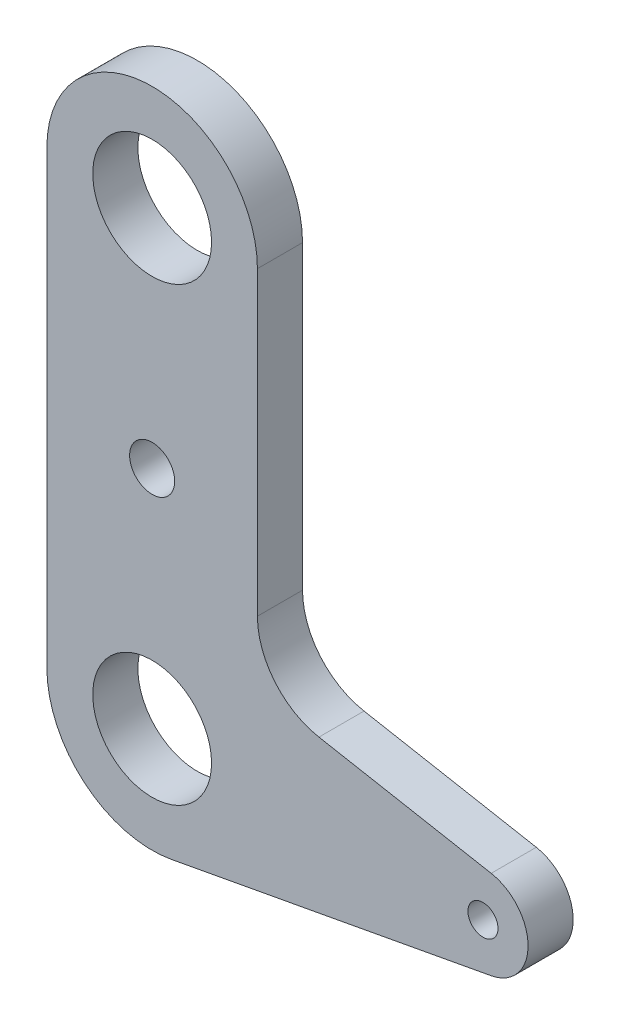
SolidWorks part; units mm, degrees
ref_plane "前视基准面" through (0, 0, 0) normal (0, 0, 1) x (1, 0, 0)
ref_plane "上视基准面" through (0, 0, 0) normal (0, 1, 0) x (1, 0, 0)
ref_plane "右视基准面" through (0, 0, 0) normal (1, 0, 0) x (0, 0, -1)
sketch "草图1" plane through (0, 0, 0) normal (0, 0, 1) x (1, 0, 0)
  line L0 (-7, 30) -> (-7, 0)
  line L1 (7, 30) -> (7, 0)
  line L2 (1.2727, 6.8833) -> (22.5455, 2.95)
  line L3 (0, 0) -> (16.3963, 0)
  line L4 (1.2727, -6.8833) -> (22.5455, -2.95)
  circle A0 centre (0, 0) radius 3.95
  circle A1 centre (0, 30) radius 3.95
  circle A3 centre (0, 30) radius 7
  circle A4 centre (0, 0) radius 7
  circle A6 centre (22, 0) radius 1
  circle A7 centre (22, 0) radius 3
  circle A8 centre (0, 15) radius 1.5
  dimension "D1" = 14
  dimension "D2" = 7.9
  dimension "D3" = 30
  dimension "D4" = 22
  dimension "D5" = 6
  dimension "D6" = 2
  dimension "D7" = 3
  dimension "D9" = 7.9
  dimension "D8" = 15
extrude "凸台-拉伸1" add sketch "草图1" along normal blind 3
fillet "圆角1" radius 5 1 edges at (7, 5.8244, 1.5)
